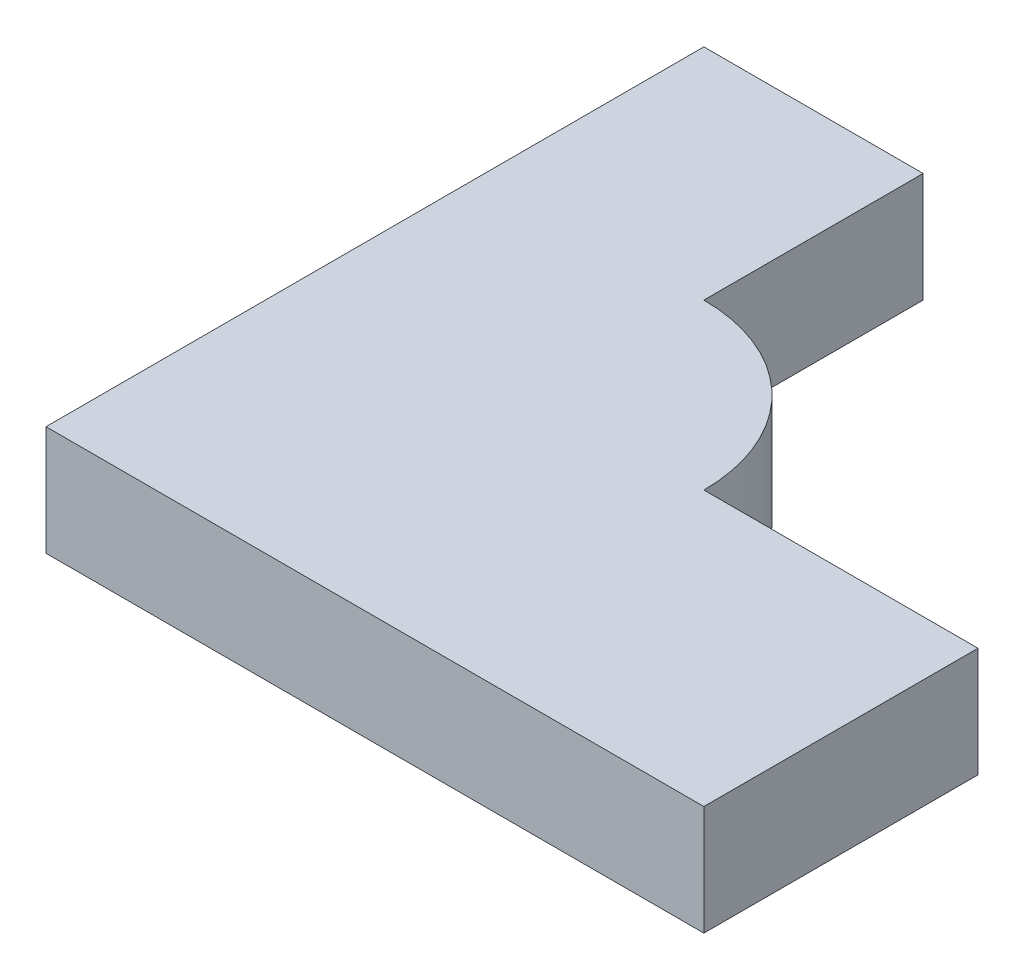
SolidWorks part; units mm, degrees
ref_plane "Front Plane" through (0, 0, 0) normal (0, 0, 1) x (1, 0, 0)
ref_plane "Top Plane" through (0, 0, 0) normal (0, 1, 0) x (1, 0, 0)
ref_plane "Right Plane" through (0, 0, 0) normal (1, 0, 0) x (0, 0, -1)
sketch "Sketch1" plane through (0, 0, 0) normal (0, 1, 0) x (1, 0, 0)
  line L0 (0, 0) -> (60, 0)
  line L1 (60, 0) -> (60, 25)
  line L2 (60, 25) -> (35, 25)
  line L3 (20, 40) -> (20, 60)
  line L4 (20, 60) -> (0, 60)
  line L5 (0, 60) -> (0, 0)
  arc A0 (35, 25) -> (20, 40) centre (20, 25) ccw
extrude "Boss-Extrude1" add sketch "Sketch1" along normal blind 10
